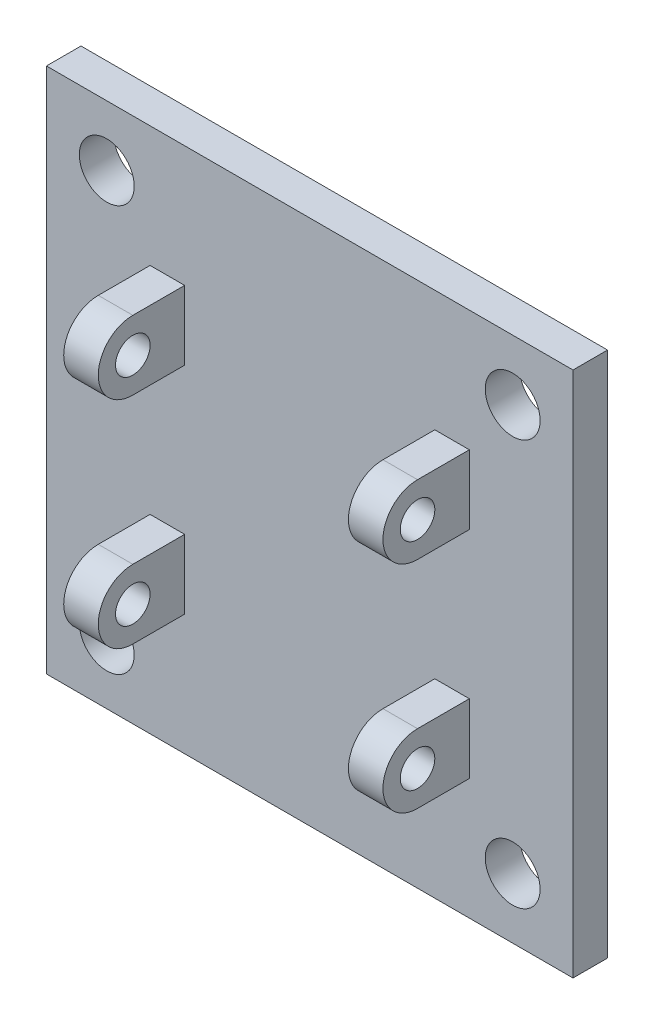
SolidWorks part; units mm, degrees
ref_plane "Alzado" through (0, 0, 0) normal (0, 0, 1) x (1, 0, 0)
ref_plane "Planta" through (0, 0, 0) normal (0, 1, 0) x (1, 0, 0)
ref_plane "Vista lateral" through (0, 0, 0) normal (1, 0, 0) x (0, 0, -1)
sketch "Croquis1" plane through (0, 0, 0) normal (0, 0, 1) x (1, 0, 0)
  line L1 (0, 0) -> (152.4, 0)
  line L2 (0, 0) -> (0, 152.4)
  line L3 (0, 152.4) -> (152.4, 152.4)
  line L4 (152.4, 0) -> (152.4, 152.4)
  dimension "D1" = 152.4
extrude "Saliente-Extruir1" add sketch "Croquis1" along normal blind 10
sketch "Croquis2" plane through (0, 0, 10) normal (0, 0, 1) x (1, 0, 0)
  line L0 (152.4, 152.4) -> (0, 0) construction
  line L1 (0, 76.2) -> (152.4, 76.2) construction
  line L2 (152.4, 0) -> (0, 152.4) construction
  line L3 (0, 152.4) -> (0, 0) construction
  line L4 (152.4, 0) -> (152.4, 152.4) construction
  circle A0 centre (134.94, 17.46) radius 7.94
  circle A1 centre (17.46, 17.46) radius 7.94
  circle A2 centre (134.94, 134.94) radius 7.94
  circle A3 centre (17.46, 134.94) radius 7.94
  dimension "D1" = 15.88
  dimension "D2" = 117.48
extrude "Cortar-Extruir1" cut sketch "Croquis2" against normal through all
ref_plane "Plano1" through (40, 0, 0) normal (-1, 0, 0) x (0, 0, 1)
sketch "Croquis4" plane through (40, 0, 0) normal (-1, 0, 0) x (0, 0, 1)
  line L0 (10, 117.4) -> (25, 117.4)
  line L1 (10, 152.4) -> (10, 0) construction
  line L2 (25, 97.4) -> (10, 97.4)
  line L3 (10, 97.4) -> (10, 117.4)
  line L4 (10, 152.4) -> (0, 152.4) construction
  line L5 (0, 76.2) -> (35.7967, 76.2) construction
  line L6 (0, 152.4) -> (0, 0) construction
  line L7 (25, 55) -> (10, 55)
  line L8 (10, 35) -> (25, 35)
  line L9 (10, 55) -> (10, 35)
  arc A0 (25, 117.4) -> (25, 97.4) centre (25, 107.4) cw
  circle A1 centre (25, 107.4) radius 5
  circle A2 centre (25, 45) radius 5
  arc A3 (25, 35) -> (25, 55) centre (25, 45) ccw
  dimension "D1" = 5
  dimension "D2" = 15
  dimension "D3" = 45
  dimension "D4" = 20
extrude "Saliente-Extruir2" add sketch "Croquis4" along normal blind 10
ref_plane "Plano2" through (76.2, 0, 0) normal (-1, 0, 0) x (0, 0, 1)
mirror "Simetría1" about plane through (76.2, 0, 0) normal (-1, 0, 0) of "Saliente-Extruir2"
